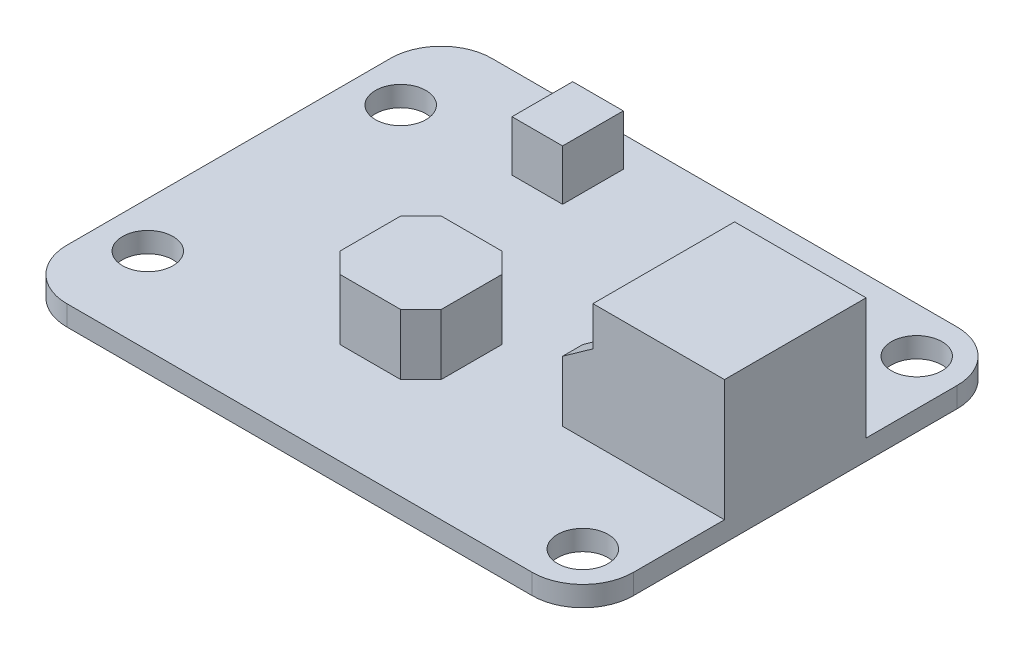
SolidWorks part; units mm, degrees
ref_plane "Alzado" through (0, 0, 0) normal (0, 0, 1) x (1, 0, 0)
ref_plane "Planta" through (0, 0, 0) normal (0, 1, 0) x (1, 0, 0)
ref_plane "Vista lateral" through (0, 0, 0) normal (1, 0, 0) x (0, 0, -1)
sketch "Croquis1" plane through (0, 0, 0) normal (0, 1, 0) x (1, 0, 0)
  line L1 (-11.5, -10.5) -> (11.5, -10.5)
  line L2 (-14, -8) -> (-14, 8)
  line L3 (-11.5, 10.5) -> (11.5, 10.5)
  line L4 (14, -8) -> (14, 8)
  line L5 (-14, -10.5) -> (14, 10.5) construction
  line L6 (-14, 10.5) -> (14, -10.5) construction
  arc A0 (11.5, 10.5) -> (14, 8) centre (11.5, 8) cw
  arc A1 (11.5, -10.5) -> (14, -8) centre (11.5, -8) ccw
  arc A2 (-11.5, -10.5) -> (-14, -8) centre (-11.5, -8) cw
  arc A3 (-14, 8) -> (-11.5, 10.5) centre (-11.5, 8) cw
  circle A4 centre (11.75, -8.25) radius 1.25
  circle A5 centre (11.75, 8.25) radius 1.25
  circle A6 centre (-11.75, 6.25) radius 1.25
  circle A7 centre (-11.75, -6.25) radius 1.25
  point P0 (0, 0)
  dimension "D3" = 2.5
  dimension "D4" = 2.5
  dimension "D5" = 2.5
  dimension "D6" = 2.5
  dimension "D7" = 2.5
  dimension "D1" = 28
  dimension "D2" = 21
  dimension "D8" = 2.25
  dimension "D9" = 2.25
  dimension "D11" = 2.25
  dimension "D12" = 4.25
  dimension "D13" = 4.25
  dimension "D14" = 2.25
extrude "Saliente-Extruir1" add sketch "Croquis1" along normal blind 1
sketch "Croquis2" plane through (0, 1, 0) normal (0, 1, 0) x (1, 0, 0)
  line L0 (11.5, 10.5) -> (-11.5, 10.5) construction
  line L1 (14, -3.5) -> (6, -3.5)
  line L2 (14, -3.5) -> (14, 3.5)
  line L3 (14, 3.5) -> (6, 3.5)
  line L4 (6, -3.5) -> (6, -2.5)
  line L5 (14, -3.5) -> (6, 3.5) construction
  line L6 (14, 3.5) -> (6, -3.5) construction
  line L8 (14, -8) -> (14, 8) construction
  line L9 (6, 2.5) -> (7.5, 2.5)
  line L10 (7.5, 2.5) -> (7.5, -2.5)
  line L11 (7.5, -2.5) -> (6, -2.5)
  line L12 (6, 2.5) -> (6, 3.5)
  point P0 (10, 0)
  dimension "D1" = 8
  dimension "D2" = 7
  dimension "D3" = 7
  dimension "D4" = 1
  dimension "D5" = 1
  dimension "D6" = 1.5
extrude "Saliente-Extruir2" add sketch "Croquis2" along normal blind 6
sketch "Croquis3" plane through (0, 0, 3.5) normal (0, 0, 1) x (1, 0, 0)
  line L0 (7.5, 7) -> (7.5, 5.064)
  line L1 (7.5, 5.064) -> (6, 4)
  line L2 (6, 7) -> (6, 1) construction
  line L3 (6, 4) -> (6, 7)
  line L4 (6, 7) -> (7.5, 7)
  line L5 (-11.5, 1) -> (11.5, 1) construction
  dimension "D1" = 3
extrude "Cortar-Extruir1" cut sketch "Croquis3" against normal through all
sketch "Croquis4" plane through (0, 1, 0) normal (0, 1, 0) x (1, 0, 0)
  line L0 (-14, 8) -> (-14, -8) construction
  line L1 (-3, -5.5) -> (0, -5.5)
  line L2 (-4, -4.5) -> (-4, -1.5)
  line L3 (-3, -0.5) -> (0, -0.5)
  line L4 (1, -4.5) -> (1, -1.5)
  line L5 (-4, -5.5) -> (1, -0.5) construction
  line L6 (-4, -0.5) -> (1, -5.5) construction
  line L7 (-11.5, -10.5) -> (11.5, -10.5) construction
  line L8 (-4, -1.5) -> (-3, -0.5)
  line L9 (-4, -4.5) -> (-3, -5.5)
  line L10 (0, -5.5) -> (1, -4.5)
  line L11 (1, -1.5) -> (0, -0.5)
  point P0 (-1.5, -3)
  dimension "D1" = 10
  dimension "D2" = 5
  dimension "D3" = 5
  dimension "D4" = 1
  dimension "D5" = 1
  dimension "D6" = 1
  dimension "D7" = 1
  dimension "D8" = 1
  dimension "D9" = 1
  dimension "D10" = 1
  dimension "D11" = 1
  dimension "D12" = 5
extrude "Saliente-Extruir3" add sketch "Croquis4" along normal blind 3
sketch "Croquis5" plane through (0, 1, 0) normal (0, 1, 0) x (1, 0, 0)
  line L0 (11.5, 10.5) -> (-11.5, 10.5) construction
  line L1 (-6, 9) -> (-3.5, 9)
  line L2 (-6, 9) -> (-6, 6)
  line L3 (-6, 6) -> (-3.5, 6)
  line L4 (-3.5, 9) -> (-3.5, 6)
  line L5 (-6, 9) -> (-3.5, 6) construction
  line L6 (-6, 6) -> (-3.5, 9) construction
  line L7 (-14, 8) -> (-14, -8) construction
  point P0 (-4.75, 7.5)
  dimension "D1" = 1.5
  dimension "D2" = 8
  dimension "D3" = 2.5
  dimension "D4" = 3
extrude "Saliente-Extruir4" add sketch "Croquis5" along normal blind 2.5
